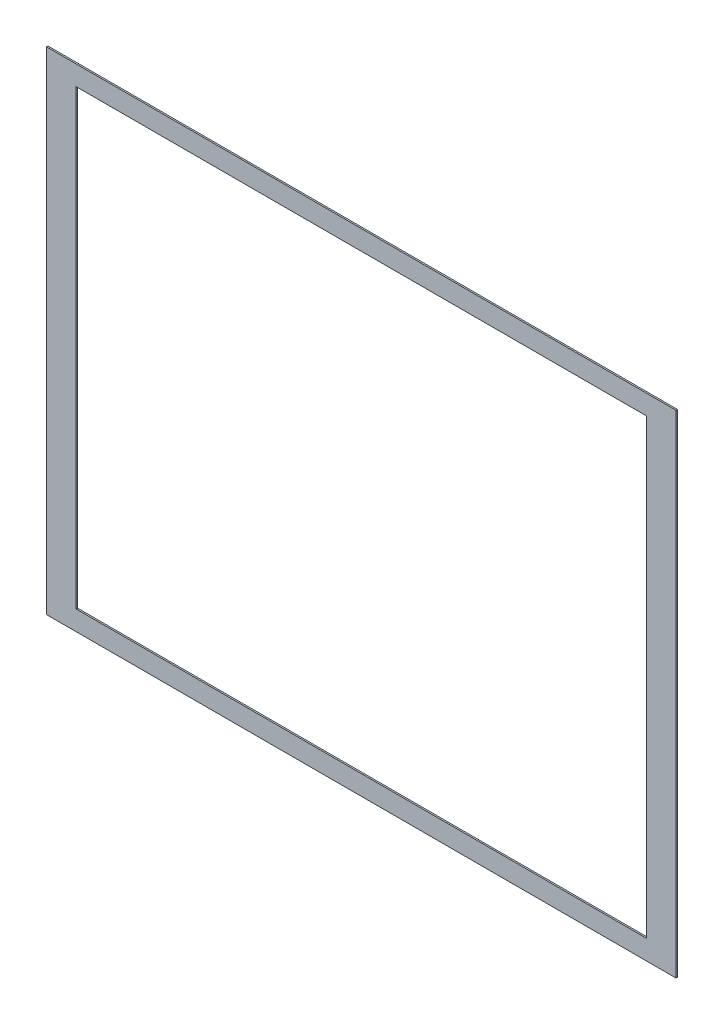
SolidWorks part; units mm, degrees
ref_plane "Front Plane" through (0, 0, 0) normal (0, 0, 1) x (1, 0, 0)
ref_plane "Top Plane" through (0, 0, 0) normal (0, 1, 0) x (1, 0, 0)
ref_plane "Right Plane" through (0, 0, 0) normal (1, 0, 0) x (0, 0, -1)
other "Configuration Table"
sketch "Sketch1" plane through (0, 0, 0) normal (0, 0, 1) x (1, 0, 0)
  line L1 (30, 320) -> (670, 320)
  line L2 (30, 320) -> (30, 820)
  line L3 (30, 820) -> (670, 820)
  line L4 (670, 320) -> (670, 820)
extrude "OVEN_panel_kesme_1" add sketch "Sketch1" along normal blind 1.5 from offset 38.5 separate body
sketch "Sketch2" plane through (0, 0, 0) normal (0, 0, 1) x (1, 0, 0)
  line L1 (60, 340) -> (640, 340)
  line L2 (60, 340) -> (60, 800)
  line L3 (60, 800) -> (640, 800)
  line L4 (640, 340) -> (640, 800)
extrude "OVEN_panel_kesme_2" cut sketch "Sketch2" along normal blind 3.5 from offset 37.5
